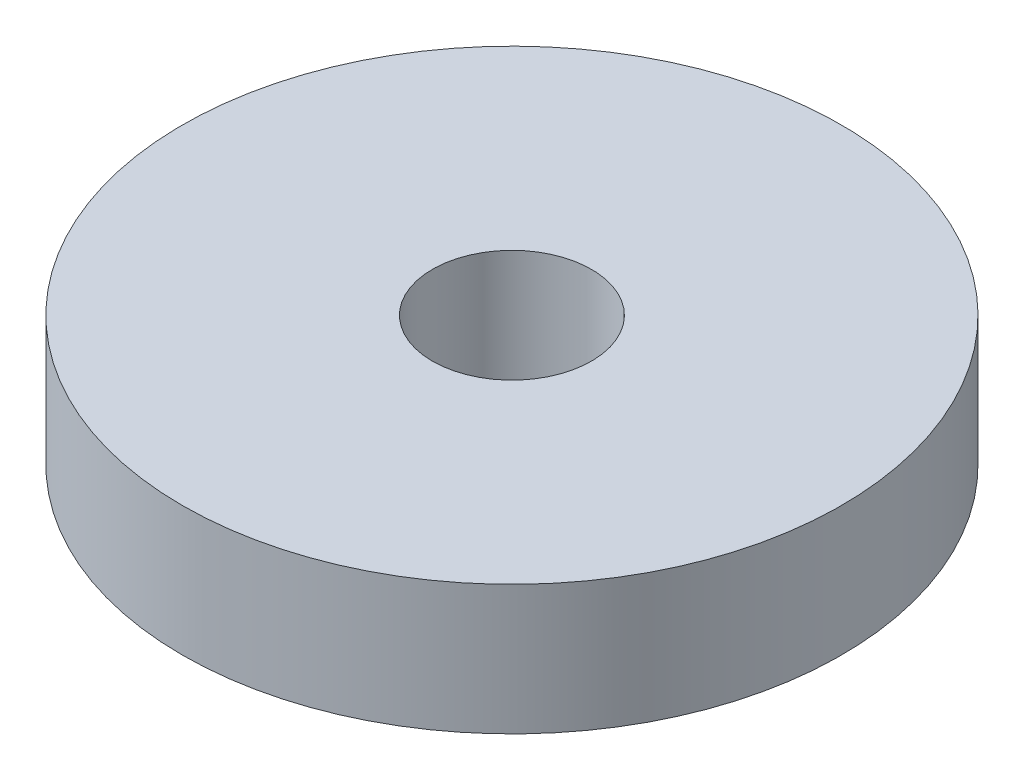
SolidWorks part; units mm, degrees
ref_plane "Front" through (0, 0, 0) normal (0, 0, 1) x (1, 0, 0)
ref_plane "Top" through (0, 0, 0) normal (0, 1, 0) x (1, 0, 0)
ref_plane "Right" through (0, 0, 0) normal (1, 0, 0) x (0, 0, -1)
sketch "Sketch1" plane through (0, 0, 0) normal (0, 1, 0) x (1, 0, 0)
  circle A0 centre (0, 0) radius 7.25
  circle A1 centre (0, 0) radius 1.75
  dimension "D1" = 14.5
  dimension "D2" = 3.5
extrude "Boss-Extrude1" add sketch "Sketch1" along normal blind 2.85
